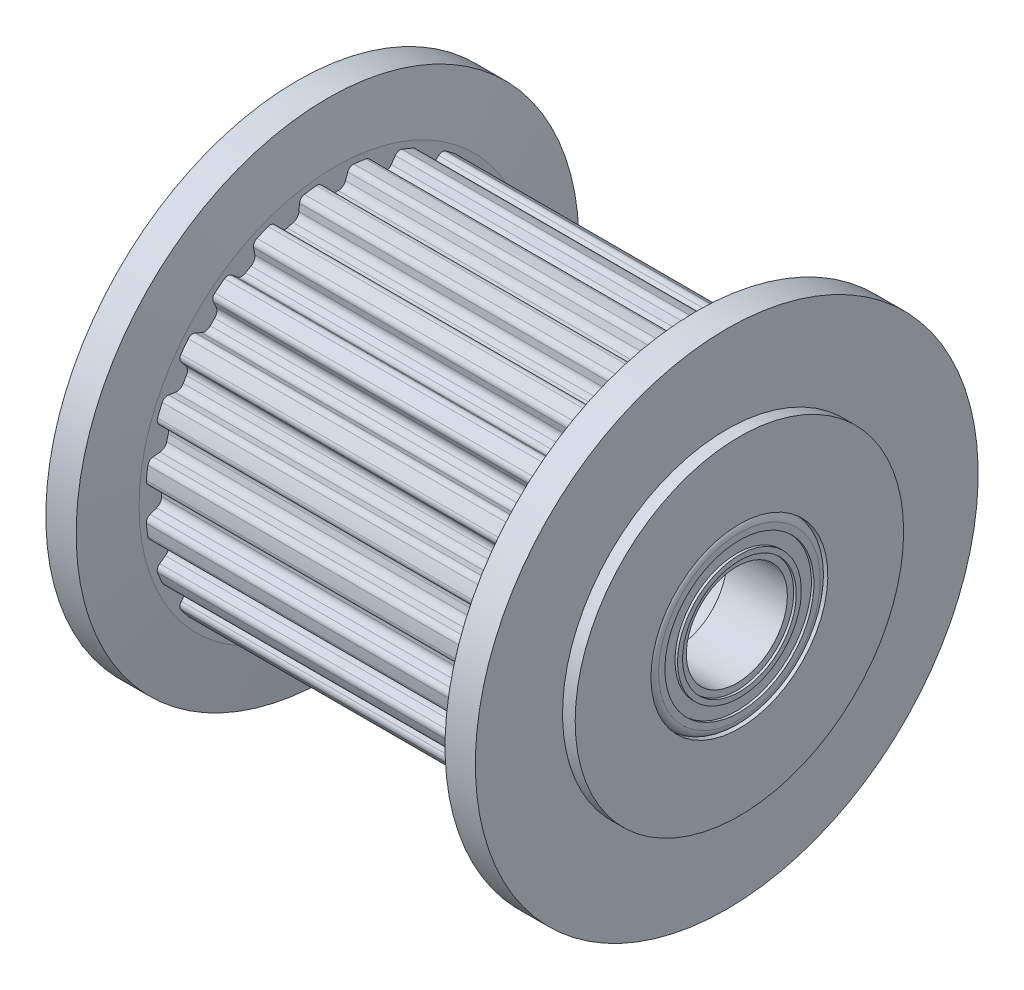
SolidWorks part; units mm, degrees
ref_plane "前视基准面" through (0, 0, 0) normal (0, 0, 1) x (1, 0, 0)
ref_plane "上视基准面" through (0, 0, 0) normal (0, 1, 0) x (1, 0, 0)
ref_plane "右视基准面" through (0, 0, 0) normal (1, 0, 0) x (0, 0, -1)
sketch "草图1" plane through (0, 0, 0) normal (0, 0, 1) x (1, 0, 0)
  line L0 (-9, 0) -> (-9, 6.5)
  line L1 (-9, 6.5) -> (-7, 6.5)
  line L2 (-7, 6.5) -> (-7, 7.51)
  line L3 (-7, 7.51) -> (7, 7.51)
  line L4 (7, 7.51) -> (7, 6.5)
  line L5 (7, 6.5) -> (9, 6.5)
  line L6 (9, 6.5) -> (9, 0)
  line L7 (9, 0) -> (-9, 0)
  dimension "D1" = 14
  dimension "D2" = 18
  dimension "D3" = 6.5
  dimension "D4" = 7.51
revolve "旋转1" add sketch "草图1" angle 360 about L7
sketch "草图3" plane through (-7, 0, 0) normal (-1, 0, 0) x (0, 0, 1)
  line L0 (-0.5632, 7.4889) -> (-0.335, 6.8618)
  line L1 (0.5632, 7.4889) -> (0.335, 6.8618)
  line L2 (0, 6.87) -> (0, 7.51) construction
  arc A0 (0.335, 6.8618) -> (-0.335, 6.8618) centre (0, 0) ccw
  arc A1 (0.5632, 7.4889) -> (-0.5632, 7.4889) centre (0, 0) ccw
  circle A2 centre (0, 0) radius 7.51 construction
  dimension "D2" = 0.64
  dimension "D1" = 20
  dimension "D3" = 0.67
extrude "切除-拉伸1" cut sketch "草图3" against normal through all
fillet "圆角1" radius 0.3 2 edges at (0, 6.8618, 0.335) (0, 6.8618, -0.335)
fillet "圆角2" radius 0.23 2 edges at (0, 7.4889, 0.5632) (0, 7.4889, -0.5632)
pattern_circular "阵列(圆周)1" count 24 over 360 about axis through (0, 0, 0) along (1, 0, 0) of "切除-拉伸1", "圆角2", "圆角1"
sketch "草图4" plane through (-7, 0, 0) normal (-1, 0, 0) x (0, 0, 1)
  line L0 (0, 6.75) -> (0, 7.51) construction
  circle A0 centre (0, 0) radius 7.76 construction
  arc A2 (0.2084, 6.7468) -> (-0.2084, 6.7468) centre (0, 0) ccw
  arc A3 (-0.65, 7.4818) -> (-0.2084, 6.7468) centre (0.65, 7.7627) ccw
  circle A4 centre (0, 0) radius 7.51 construction
  arc A5 (0.65, 7.4818) -> (0.2084, 6.7468) centre (-0.65, 7.7627) cw
  arc A6 (0.65, 7.4818) -> (-0.65, 7.4818) centre (0, 0) ccw
  dimension "D1" = 15.52
  dimension "D2" = 0.76
  dimension "D4" = 1.33
  dimension "D3" = 1.3
extrude "切除-拉伸2" [suppressed] cut sketch "草图4" against normal through all
fillet "圆角3" [suppressed] radius 0.1
fillet "圆角4" [suppressed] radius 0.19
pattern_circular "阵列(圆周)2" [suppressed] count 24 over 360
sketch "草图5" plane through (0, 0, 0) normal (0, 0, 1) x (1, 0, 0)
  line L0 (-8.5, 6.5) -> (-8.5, 9.95)
  line L2 (-8.5, 9.95) -> (-7.3, 9.95)
  line L3 (-7.3, 9.95) -> (-7, 7.76)
  line L4 (-7, 7.76) -> (-7, 6.5)
  line L5 (-7, 6.5) -> (-8.5, 6.5)
  line L6 (-9, 0) -> (9, 0) construction
  line L7 (-9, 6.5) -> (-9, -6.5) construction
  line L8 (9, -6.5) -> (9, 6.5) construction
  line L9 (0, 0) -> (0, 30.9) construction
  line L11 (-7, 7.51) -> (-7, -7.51) construction
  line L12 (8.5, 9.95) -> (7.3, 9.95)
  line L13 (7.3, 9.95) -> (7, 7.76)
  line L14 (7, 7.76) -> (7, 6.5)
  line L15 (8.5, 6.5) -> (8.5, 9.95)
  line L16 (7, 6.5) -> (8.5, 6.5)
  dimension "D1" = 9.95
  dimension "D2" = 7.76
  dimension "D3" = 0.5
  dimension "D4" = 1.2
  dimension "D5" = 6.5
revolve "旋转2" add sketch "草图5" angle 360 about L6
sketch "草图6" plane through (0, 0, 0) normal (0, 0, 1) x (1, 0, 0)
  line L0 (-9, 3.5) -> (-6.5, 3.5)
  line L1 (-9, 6.5) -> (-9, -6.5) construction
  line L2 (-6.5, 3.5) -> (-6.5, 3)
  line L3 (-6.5, 3) -> (6.5, 3)
  line L4 (6.5, 3) -> (6.5, 3.5)
  line L5 (6.5, 3.5) -> (9, 3.5)
  line L6 (9, -6.5) -> (9, 6.5) construction
  line L7 (9, 3.5) -> (9, 0)
  line L8 (9, 0) -> (-9, 0)
  line L9 (-9, 0) -> (-9, 3.5)
  dimension "D1" = 3.5
  dimension "D2" = 3
  dimension "D3" = 2.5
revolve "切除-旋转1" cut sketch "草图6" angle 360 about L8
sketch "草图7" plane through (0, 0, 0) normal (0, 0, 1) x (1, 0, 0)
  line L0 (-9, 6.5) -> (-9, -6.5) construction
  line L1 (-9, 0) -> (-6.5, 0)
  line L2 (-9, 0) -> (-9, 3.2)
  line L3 (-8.7, 3.5) -> (-6.8, 3.5)
  line L4 (-6.5, 0) -> (-6.5, 3.2)
  line L5 (9, -6.5) -> (9, 6.5) construction
  line L6 (9, 0) -> (6.5, 0)
  line L7 (9, 0) -> (9, 3.2)
  line L8 (8.7, 3.5) -> (6.8, 3.5)
  line L9 (6.5, 0) -> (6.5, 3.2)
  arc A0 (9, 3.2) -> (8.7, 3.5) centre (8.7, 3.2) ccw
  arc A1 (6.8, 3.5) -> (6.5, 3.2) centre (6.8, 3.2) ccw
  arc A2 (-6.5, 3.2) -> (-6.8, 3.5) centre (-6.8, 3.2) ccw
  arc A3 (-8.7, 3.5) -> (-9, 3.2) centre (-8.7, 3.2) ccw
  point P20 (-9, 3.5)
  dimension "D3" = 0.3
  dimension "D1" = 2.5
  dimension "D2" = 3.5
revolve "旋转3" add sketch "草图7" angle 360 about L1
sketch "草图8" plane through (-9, 0, 0) normal (-1, 0, 0) x (0, 0, 1)
  circle A0 centre (0, 0) radius 2
  dimension "D1" = 4
extrude "切除-拉伸3" cut sketch "草图8" against normal through all
sketch "草图9" plane through (0, 0, 0) normal (0, 0, 1) x (1, 0, 0)
  line L0 (-9, 6.5) -> (-9, -6.5) construction
  line L1 (-9, 2.25) -> (-8.9, 2.25)
  line L2 (-9, 2.25) -> (-9, 1.75)
  line L3 (-9, 1.75) -> (-8.9, 1.75)
  line L4 (-8.9, 2.25) -> (-8.9, 1.75)
  line L5 (-9, 0) -> (9, 0) construction
  line L6 (9, -6.5) -> (9, 6.5) construction
  line L8 (9, 1.75) -> (8.9, 1.75)
  line L9 (9, 1.75) -> (9, 2.25)
  line L10 (9, 2.25) -> (8.9, 2.25)
  line L11 (8.9, 1.75) -> (8.9, 2.25)
  line L12 (-9, 2.45) -> (-8.9, 2.45)
  line L13 (-9, 2.45) -> (-9, 2.95)
  line L14 (-9, 2.95) -> (-8.9, 2.95)
  line L15 (-8.9, 2.45) -> (-8.9, 2.95)
  line L16 (9, 2.45) -> (8.9, 2.45)
  line L17 (9, 2.45) -> (9, 2.95)
  line L18 (9, 2.95) -> (8.9, 2.95)
  line L19 (8.9, 2.45) -> (8.9, 2.95)
  dimension "D1" = 0.1
  dimension "D2" = 0.5
  dimension "D3" = 1.75
  dimension "D4" = 2.45
revolve "切除-旋转2" cut sketch "草图9" angle 360 about L5
